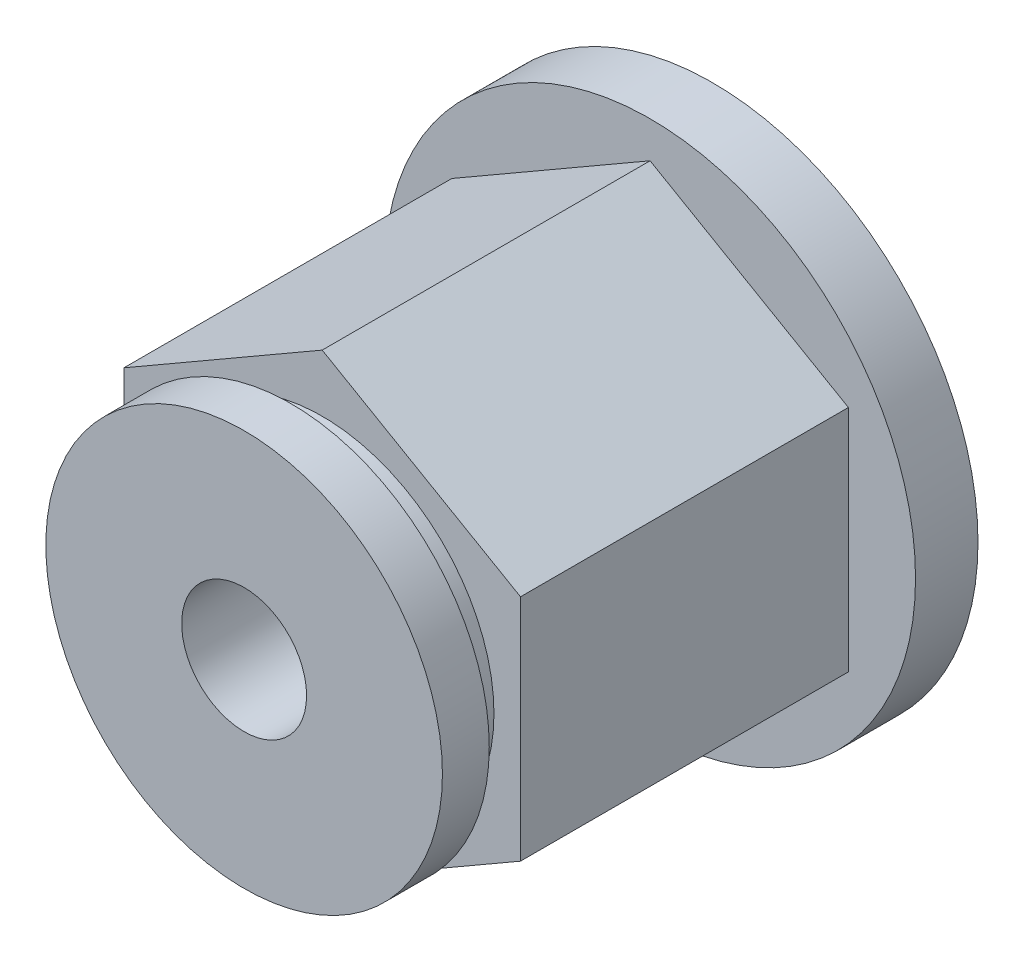
SolidWorks part; units mm, degrees
ref_plane "Plan de face" through (0, 0, 0) normal (0, 0, 1) x (1, 0, 0)
ref_plane "Plan de dessus" through (0, 0, 0) normal (0, 1, 0) x (1, 0, 0)
ref_plane "Plan de droite" through (0, 0, 0) normal (1, 0, 0) x (0, 0, -1)
sketch "Esquisse1" plane through (0, 0, 0) normal (0, 0, 1) x (1, 0, 0)
  circle A0 centre (0, 0) radius 8.5
  dimension "D1" = 17
extrude "Boss.-Extru.1" add sketch "Esquisse1" along normal blind 2
sketch "Esquisse2" plane through (0, 0, 2) normal (0, 0, 1) x (1, 0, 0)
  line L1 (6.35, -3.6662) -> (6.35, 3.6662)
  line L2 (6.35, 3.6662) -> (0, 7.3323)
  line L3 (0, 7.3323) -> (-6.35, 3.6662)
  line L4 (-6.35, 3.6662) -> (-6.35, -3.6662)
  line L5 (-6.35, -3.6662) -> (0, -7.3323)
  line L6 (0, -7.3323) -> (6.35, -3.6662)
  circle A0 centre (0, 0) radius 6.35 construction
  dimension "D1" = 12.7
extrude "Boss.-Extru.2" add sketch "Esquisse2" along normal blind 10.5
sketch "Esquisse3" plane through (0, 0, 12.5) normal (0, 0, 1) x (1, 0, 0)
  circle A0 centre (0, 0) radius 5.5
  dimension "D1" = 11
extrude "Boss.-Extru.3" add sketch "Esquisse3" along normal blind 1
sketch "Esquisse4" plane through (0, 0, 13.5) normal (0, 0, 1) x (1, 0, 0)
  circle A0 centre (0, 0) radius 6.35
extrude "Boss.-Extru.4" add sketch "Esquisse4" along normal blind 1.5
sketch "Esquisse5" plane through (0, 0, 15) normal (0, 0, 1) x (1, 0, 0)
  circle A0 centre (0, 0) radius 2
extrude "Enlèv. mat.-Extru.1" cut sketch "Esquisse5" against normal through all
